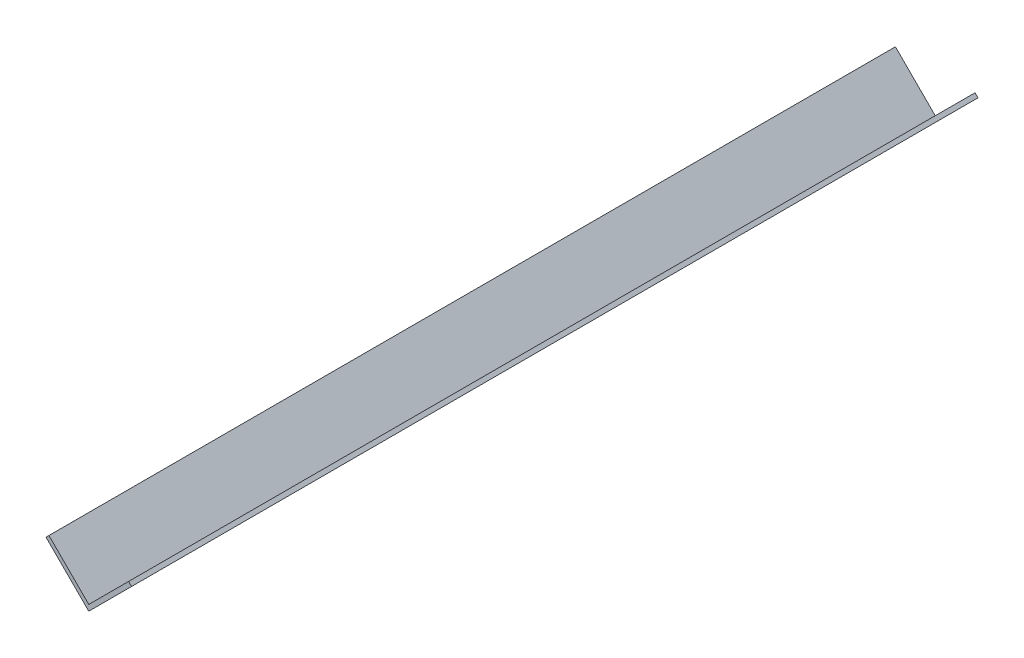
SolidWorks part; units mm, degrees
material "6061 Alloy"
ref_plane "Front Plane" through (0, 0, 0) normal (0, 0, 1) x (1, 0, 0)
ref_plane "Top Plane" through (0, 0, 0) normal (0, 1, 0) x (1, 0, 0)
ref_plane "Right Plane" through (0, 0, 0) normal (1, 0, 0) x (0, 0, -1)
sketch "Sketch1" plane through (0, 0, 0) normal (0, 0, 1) x (1, 0, 0)
  line L0 (0, 0) -> (-17.9605, 17.9605)
  line L1 (-17.9605, 17.9605) -> (-16.7257, 19.1953)
  line L2 (-16.7257, 19.1953) -> (0, 2.4696)
  line L3 (0, 2.4696) -> (16.7257, 19.1953)
  line L4 (16.7257, 19.1953) -> (17.9605, 17.9605)
  line L5 (17.9605, 17.9605) -> (0, 0)
  dimension "D1" = 1.7463
  dimension "D2" = 25.4
extrude "Boss-Extrude1" add sketch "Sketch1" along normal blind 355.6
